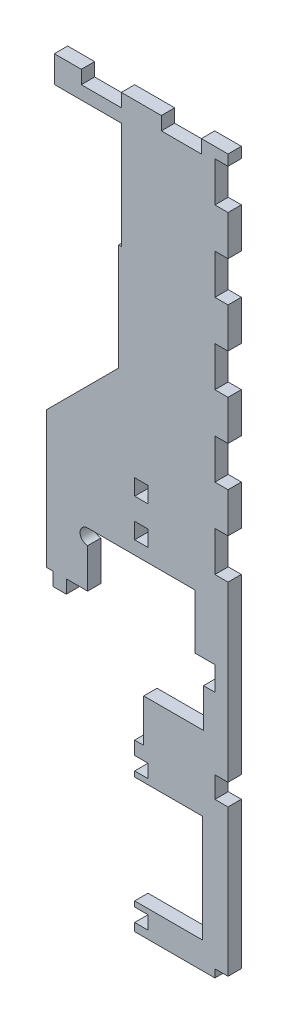
SolidWorks part; units mm, degrees
material "Balsa"
ref_plane "Plan de face" through (0, 0, 0) normal (0, 0, 1) x (1, 0, 0)
ref_plane "Plan de dessus" through (0, 0, 0) normal (0, 1, 0) x (1, 0, 0)
ref_plane "Plan de droite" through (0, 0, 0) normal (1, 0, 0) x (0, 0, -1)
sketch "Esquisse1" plane through (0, 0, 0) normal (0, 0, 1) x (1, 0, 0)
  line L0 (65.1211, 0) -> (30.1224, 0)
  line L2 (65.1211, 0) -> (65.1211, 270)
  line L3 (65.1211, 270) -> (0, 270)
  line L4 (0, 270) -> (0, 260)
  line L5 (0, 260) -> (24.1211, 260)
  line L6 (-2.8789, 101.7504) -> (12.493, 101.7504)
  line L7 (12.493, 101.7504) -> (12.493, 122.247)
  line L8 (12.493, 122.247) -> (52.693, 122.247)
  line L9 (52.693, 122.247) -> (52.693, 101.7504)
  line L10 (52.693, 101.7504) -> (55.9116, 101.7504)
  line L11 (1.3186, 101.7504) -> (30.1224, 101.7504) construction
  line L12 (55.9116, 101.7504) -> (55.9116, 78.2407)
  line L13 (55.9116, 78.2407) -> (33.5123, 78.2407)
  line L14 (33.5123, 78.2407) -> (33.5123, 62.2)
  line L15 (33.5123, 62.2) -> (30.1224, 62.2)
  line L16 (30.1224, 62.2) -> (30.1224, 57.2)
  line L17 (30.1224, 50.2) -> (55.6176, 50.2)
  line L18 (30.1224, 57.2) -> (35.1224, 57.2)
  line L19 (24.1211, 260) -> (24.1211, 180)
  line L20 (35.1224, 57.2) -> (35.1224, 52.2)
  line L21 (24.1211, 180) -> (-2.8789, 153)
  line L22 (-2.8789, 153) -> (-2.8789, 101.7504)
  line L23 (35.1224, 52.2) -> (30.1224, 52.2)
  line L24 (30.1224, 52.2) -> (30.1224, 50.2)
  line L25 (30.1224, 0) -> (30.1224, 3)
  line L26 (30.1224, 3) -> (35.1224, 3)
  line L27 (35.1224, 3) -> (35.1224, 8)
  line L30 (35.1224, 8) -> (30.1224, 8)
  line L31 (30.1224, 8) -> (30.1224, 10)
  line L32 (30.1224, 10) -> (55.6176, 10)
  line L33 (55.6176, 10) -> (55.6176, 50.2)
  dimension "D1" = 270
  dimension "D2" = 65.1211
  dimension "D3" = 40.2
  dimension "D4" = 2
  dimension "D5" = 20.4965
  dimension "D6" = 40.2
  dimension "D7" = 80
  dimension "D8" = 10
  dimension "D9" = 12.4281
  dimension "D10" = 25.4952
  dimension "D11" = 5
  dimension "D12" = 5
  dimension "D13" = 5
  dimension "D14" = 2
  dimension "D15" = 5
  dimension "D16" = 5
  dimension "D17" = 25.4952
  dimension "D18" = 135
  dimension "D19" = 41
  dimension "D20" = 68
extrude "Boss.-Extru.1" add sketch "Esquisse1" against normal blind 5
sketch "Esquisse2" plane through (0, 0, 0) normal (0, 0, 1) x (1, 0, 0)
  line L0 (52.693, 101.7504) -> (55.9116, 101.7504) construction
  line L1 (35.1224, 147.4016) -> (30.1224, 147.4016)
  line L2 (12.493, 122.247) -> (52.693, 122.247) construction
  line L3 (12.493, 101.7504) -> (12.493, 122.247) construction
  line L4 (35.1224, 147.4016) -> (35.1224, 141.4016)
  line L5 (35.1224, 141.4016) -> (30.1224, 141.4016)
  line L6 (30.1224, 147.4016) -> (30.1224, 141.4016)
  line L7 (35.1224, 133.247) -> (30.1224, 133.247)
  line L8 (35.1224, 133.247) -> (35.1224, 127.247)
  line L9 (35.1224, 127.247) -> (30.1224, 127.247)
  line L10 (30.1224, 133.247) -> (30.1224, 127.247)
  line L11 (55.9116, 101.7504) -> (60.186, 101.7504)
  line L12 (55.9116, 101.7504) -> (55.9116, 92.7704)
  line L13 (55.9116, 92.7704) -> (60.186, 92.7704)
  line L14 (60.186, 101.7504) -> (60.186, 92.7704)
  line L15 (52.693, 122.247) -> (52.693, 101.7504) construction
  line L16 (65.1211, 0) -> (65.1211, 270) construction
  line L17 (65.1211, 0) -> (60.2011, 0)
  line L18 (65.1211, 0) -> (65.1211, 3)
  line L19 (65.1211, 3) -> (60.2011, 3)
  line L20 (60.2011, 0) -> (60.2011, 3)
  line L21 (30.1224, 0) -> (65.1211, 0) construction
  line L22 (65.1211, 0) -> (65.1211, 270) construction
  line L23 (65.1211, 58) -> (60.2011, 58)
  line L24 (65.1211, 58) -> (65.1211, 66)
  line L25 (65.1211, 66) -> (60.2011, 66)
  line L26 (60.2011, 58) -> (60.2011, 66)
  line L27 (30.1224, 0) -> (65.1211, 0) construction
  line L28 (65.1211, 161) -> (60.2011, 161)
  line L29 (65.1211, 131) -> (60.2011, 131)
  line L30 (65.1211, 131) -> (65.1211, 146)
  line L31 (65.1211, 146) -> (60.2011, 146)
  line L32 (60.2011, 131) -> (60.2011, 146)
  line L33 (65.1211, 161) -> (65.1211, 176)
  line L34 (65.1211, 176) -> (60.2011, 176)
  line L35 (60.2011, 161) -> (60.2011, 176)
  line L36 (65.1211, 191) -> (60.2011, 191)
  line L37 (65.1211, 191) -> (65.1211, 206)
  line L38 (65.1211, 206) -> (60.2011, 206)
  line L39 (60.2011, 191) -> (60.2011, 206)
  line L40 (65.1211, 221) -> (60.2011, 221)
  line L41 (65.1211, 221) -> (65.1211, 236)
  line L42 (65.1211, 236) -> (60.2011, 236)
  line L43 (60.2011, 221) -> (60.2011, 236)
  line L44 (65.1211, 251) -> (60.2011, 251)
  line L45 (65.1211, 251) -> (65.1211, 266)
  line L46 (65.1211, 266) -> (60.2011, 266)
  line L47 (60.2011, 251) -> (60.2011, 266)
  line L48 (65.1211, 270) -> (0, 270) construction
  line L49 (55.1211, 265) -> (40.1211, 265)
  line L50 (55.1211, 265) -> (55.1211, 270)
  line L51 (55.1211, 270) -> (40.1211, 270)
  line L52 (40.1211, 265) -> (40.1211, 270)
  line L53 (24.1211, 260) -> (24.1211, 180) construction
  line L54 (25.1211, 265) -> (10.1211, 265)
  line L55 (25.1211, 265) -> (25.1211, 270)
  line L56 (25.1211, 270) -> (10.1211, 270)
  line L57 (10.1211, 265) -> (10.1211, 270)
  line L58 (24.1211, 260) -> (25.1211, 260)
  line L59 (24.1211, 260) -> (24.1211, 220)
  line L60 (24.1211, 220) -> (25.1211, 220)
  line L61 (25.1211, 260) -> (25.1211, 220)
  line L62 (0, 260) -> (24.1211, 260) construction
  circle A0 centre (12.493, 119.3895) radius 2.8575
  dimension "D1" = 2.8575
  dimension "D2" = 7.493
  dimension "D3" = 4.92
  dimension "D4" = 3
  dimension "D5" = 4.92
  dimension "D6" = 8
  dimension "D7" = 58
  dimension "D8" = 15
  dimension "D9" = 131
  dimension "D11" = 40
  dimension "D12" = 1
  dimension "D10" = 5
extrude "Enlèv. mat.-Extru.1" cut sketch "Esquisse2" against normal blind 5
sketch "Esquisse3" plane through (0, 0, 0) normal (0, 0, 1) x (1, 0, 0)
  line L1 (4.493, 101.7504) -> (-0.507, 101.7504)
  line L2 (4.493, 101.7504) -> (4.493, 96.7504)
  line L3 (4.493, 96.7504) -> (-0.507, 96.7504)
  line L4 (-0.507, 101.7504) -> (-0.507, 96.7504)
  line L6 (-2.8789, 101.7504) -> (12.493, 101.7504) construction
  line L7 (12.493, 101.7504) -> (12.493, 116.532) construction
  dimension "D1" = 8
  dimension "D2" = 5
  dimension "D3" = 5
extrude "Boss.-Extru.2" add sketch "Esquisse3" against normal blind 5
